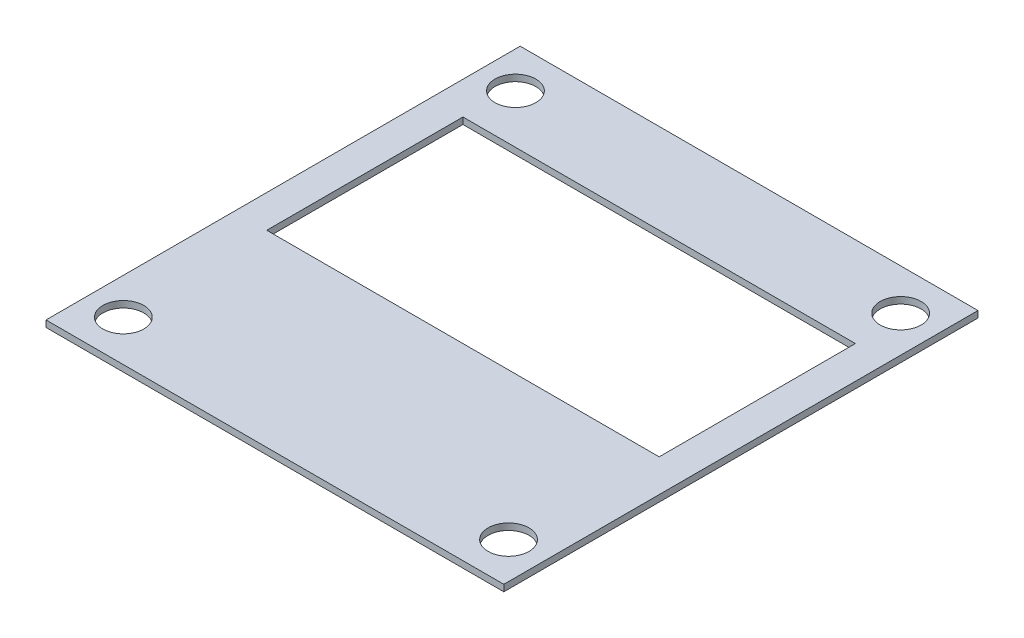
SolidWorks part; units mm, degrees
ref_plane "Plan de face" through (0, 0, 0) normal (0, 0, 1) x (1, 0, 0)
ref_plane "Plan de dessus" through (0, 0, 0) normal (0, 1, 0) x (1, 0, 0)
ref_plane "Plan de droite" through (0, 0, 0) normal (1, 0, 0) x (0, 0, -1)
sketch "Esquisse1" plane through (0, 0, 0) normal (0, 1, 0) x (1, 0, 0)
  line L1 (-14, 14.5) -> (14, 14.5)
  line L2 (-14, 14.5) -> (-14, -14.5)
  line L3 (-14, -14.5) -> (14, -14.5)
  line L4 (14, 14.5) -> (14, -14.5)
  line L5 (-14, 14.5) -> (14, -14.5) construction
  line L6 (-14, -14.5) -> (14, 14.5) construction
  line L10 (0, 0) -> (0, 3) construction
  line L11 (-12, 9) -> (12, 9)
  line L12 (-12, 9) -> (-12, -3)
  line L13 (-12, -3) -> (12, -3)
  line L14 (12, 9) -> (12, -3)
  line L15 (-12, 9) -> (12, -3) construction
  line L16 (-12, -3) -> (12, 9) construction
  point P0 (0, 0)
  point P7 (0, 3)
  dimension "D1" = 28
  dimension "D2" = 29
  dimension "D3" = 3
  dimension "D4" = 24
  dimension "D5" = 12
extrude "Boss.-Extru.1" add sketch "Esquisse1" along normal blind 0.4
sketch "Esquisse2" plane through (0, 0, 0) normal (0, -1, 0) x (1, 0, 0)
  line L1 (11.78, -11.99) -> (-11.78, -11.99) construction
  line L2 (11.78, -11.99) -> (11.78, 11.99) construction
  line L3 (11.78, 11.99) -> (-11.78, 11.99) construction
  line L4 (-11.78, -11.99) -> (-11.78, 11.99) construction
  line L5 (11.78, -11.99) -> (-11.78, 11.99) construction
  line L6 (11.78, 11.99) -> (-11.78, -11.99) construction
  circle A0 centre (11.78, -11.99) radius 1.25
  circle A2 centre (-11.78, 11.99) radius 1.25
  circle A3 centre (11.78, 11.99) radius 1.25
  circle A4 centre (-11.78, -11.99) radius 1.25
  point P0 (0, 0)
  dimension "D1" = 2.5
  dimension "D2" = 0
  dimension "D3" = 23.56
  dimension "D4" = 23.98
extrude "Enlèv. mat.-Extru.1" cut sketch "Esquisse2" against normal blind 10
